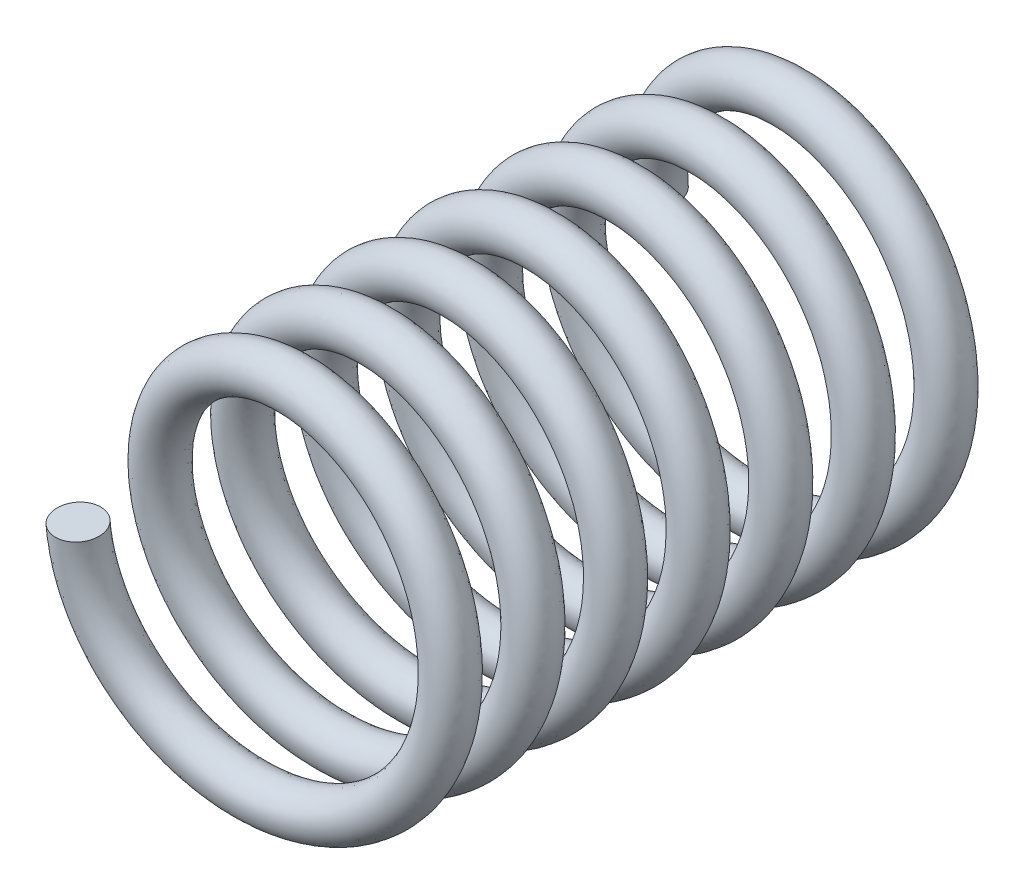
SolidWorks part; units mm, degrees
ref_plane "Ön Düzlem" through (0, 0, 0) normal (0, 0, 1) x (1, 0, 0)
ref_plane "Üst Düzlem" through (0, 0, 0) normal (0, 1, 0) x (1, 0, 0)
ref_plane "Sağ Düzlem" through (0, 0, 0) normal (1, 0, 0) x (0, 0, -1)
sketch "Çizim1" plane through (0, 0, 0) normal (0, 0, 1) x (1, 0, 0)
  circle A0 centre (0, 0) radius 10
  dimension "D1" = 20
curve "Helis/Spiral1" pitch 5 height 35 turns 7
ref_plane "Düzlem1" through (-10, 0, 35) normal (0, 0.9968, 0.0793) x (0.2646, 0.0765, -0.9613)
sketch "Çizim2" plane through (-10, 0, 35) normal (0, 0.9968, 0.0793) x (0.2646, 0.0765, -0.9613)
  circle A0 centre (0, 0) radius 1.375
  dimension "D1" = 2.75
sweep "Süpür1" add profiles "Çizim2" path "Helis/Spiral1"
